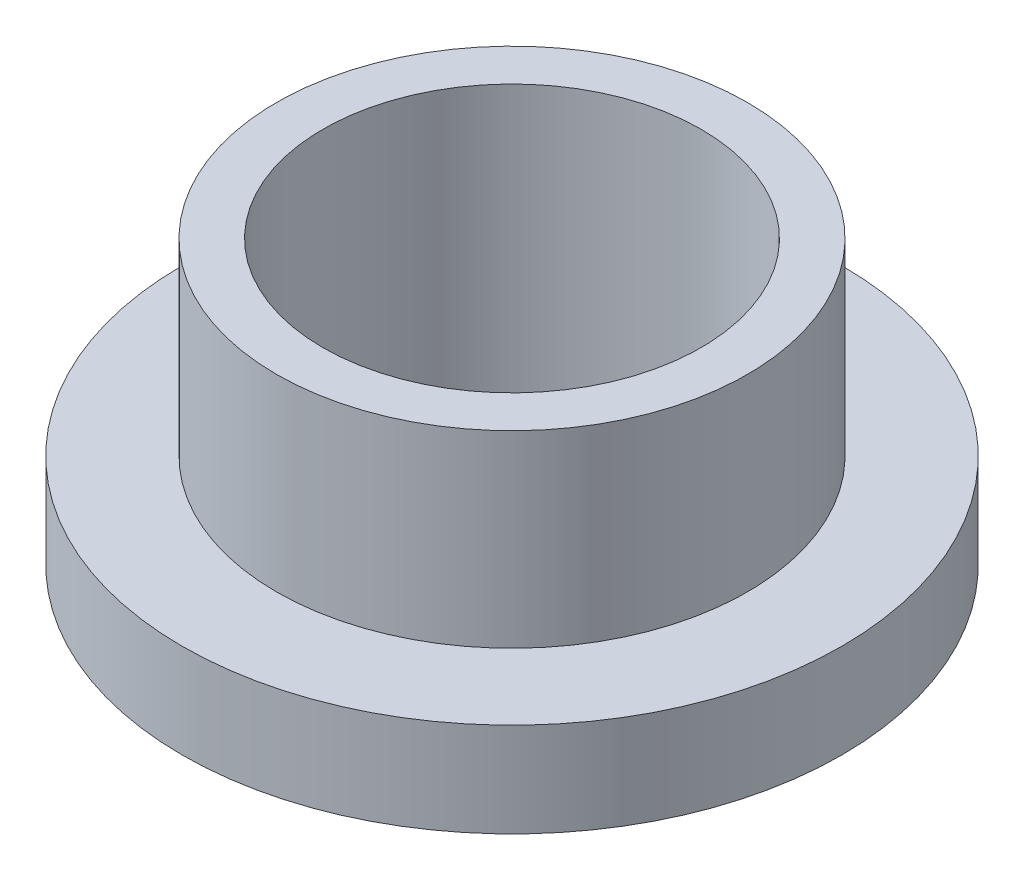
SolidWorks part; units mm, degrees
material "Tin Bearing Bronze"
ref_plane "Front" through (0, 0, 0) normal (0, 0, 1) x (1, 0, 0)
ref_plane "Top" through (0, 0, 0) normal (0, 1, 0) x (1, 0, 0)
ref_plane "Right" through (0, 0, 0) normal (1, 0, 0) x (0, 0, -1)
sketch "Sketch1" plane through (0, 0, 0) normal (0, 1, 0) x (1, 0, 0)
  circle A0 centre (0, 0) radius 6.3754
  circle A1 centre (0, 0) radius 7.9375
  circle A2 centre (0, 0) radius 11.1125
  dimension "ID" = 12.7508
  dimension "OD" = 15.875
  dimension "FlangeOD" = 22.225
sketch "Sketch2" plane through (0, 0, 0) normal (0, 1, 0) x (1, 0, 0)
  circle A0 centre (0, 0) radius 6.3754 construction
  circle A1 centre (0, 0) radius 7.9375 construction
  circle A2 centre (0, 0) radius 6.3754
  circle A3 centre (0, 0) radius 7.9375
extrude "Boss-Extrude1" add sketch "Sketch2" along normal blind 9.525
sketch "Sketch3" plane through (0, 0, 0) normal (0, 1, 0) x (1, 0, 0)
  circle A0 centre (0, 0) radius 11.1125 construction
  circle A1 centre (0, 0) radius 7.9375 construction
  circle A2 centre (0, 0) radius 11.1125
  circle A3 centre (0, 0) radius 7.9375
extrude "Boss-Extrude2" add sketch "Sketch3" along normal blind 3.175
